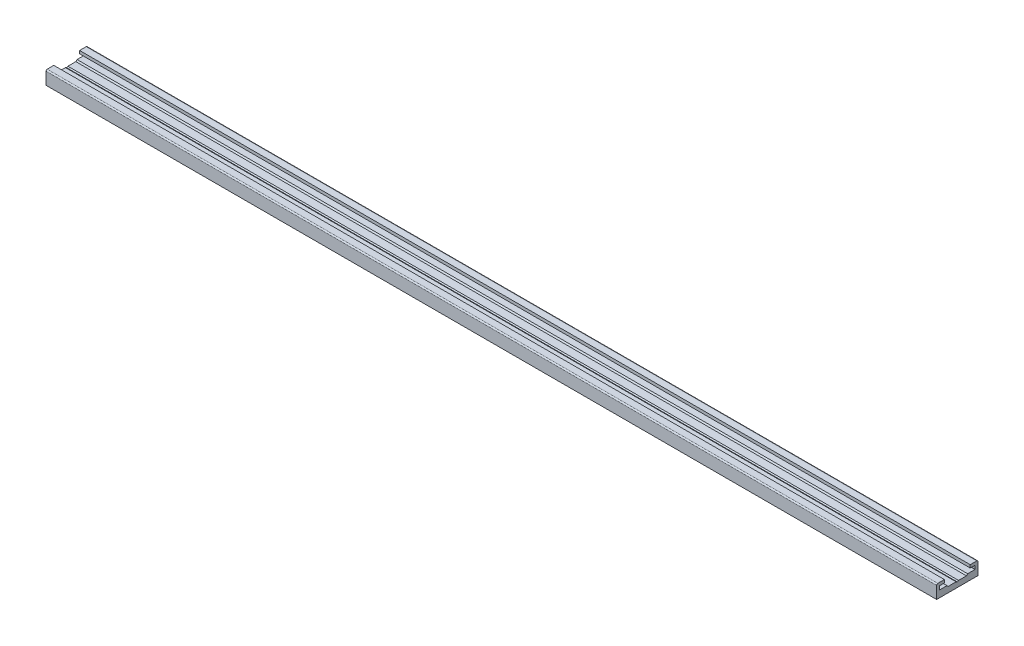
SolidWorks part; units mm, degrees
material "6061 Alloy"
ref_plane "Front" through (0, 0, 0) normal (0, 0, 1) x (1, 0, 0)
ref_plane "Top" through (0, 0, 0) normal (0, 1, 0) x (1, 0, 0)
ref_plane "Right" through (0, 0, 0) normal (1, 0, 0) x (0, 0, -1)
sketch "Sketch1" plane through (0, 0, 0) normal (1, 0, 0) x (0, 0, -1)
  line L0 (0, -2.75) -> (0, 2.75) construction
  line L1 (-0.5, -0.45) -> (0, -0.7387) construction
  line L2 (-3.75, -0.45) -> (-0.5, -0.45) construction
  line L3 (-4.25, 0.05) -> (-3.75, -0.45) construction
  line L4 (-7.3, 0.05) -> (-4.25, 0.05) construction
  line L5 (-7.3, 1.55) -> (-7.3, 0.05) construction
  line L6 (-5.3, 1.55) -> (-7.3, 1.55) construction
  line L7 (-5.3, 2.75) -> (-5.3, 1.55) construction
  line L8 (-8, 2.75) -> (-5.3, 2.75) construction
  line L9 (-8.5, -2.75) -> (-8.5, 2.25) construction
  line L39 (-8.5, -2.75) -> (8.5, -2.75) construction
  line L40 (8.5, -2.75) -> (8.5, 2.25) construction
  line L41 (8, 2.75) -> (5.3, 2.75) construction
  line L42 (5.3, 2.75) -> (5.3, 1.55) construction
  line L43 (5.3, 1.55) -> (7.3, 1.55) construction
  line L44 (7.3, 1.55) -> (7.3, 0.05) construction
  line L45 (7.3, 0.05) -> (4.25, 0.05) construction
  line L46 (4.25, 0.05) -> (3.75, -0.45) construction
  line L47 (3.75, -0.45) -> (0.5, -0.45) construction
  line L48 (0.5, -0.45) -> (0, -0.7387) construction
  arc A0 (8, 2.75) -> (8.5, 2.25) centre (8, 2.25) cw construction
  arc A1 (-8, 2.75) -> (-8.5, 2.25) centre (-8, 2.25) ccw construction
  point P1 (7.3, 0.8)
  point P26 (0, 0)
  point P32 (0, -1.75)
  dimension "D12" = 0.5
  dimension "D1" = 30
  dimension "D3" = 2.3
  dimension "Rail Height" = 5.5
  dimension "D4" = 2.0113
  dimension "D5" = 2.8
  dimension "D7" = 1.2
  dimension "D8" = 3.2
  dimension "D9" = 1.2
  dimension "D10" = 45
  dimension "D11" = 3.75
  dimension "Rail Width" = 17
  dimension "Mounting Hole Depth" = 1
sketch "Sketch2" plane through (0, 0, 0) normal (0, 0, 1) x (1, 0, 0)
  line L0 (1000, 0) -> (-1000, 0) construction
  point P0 (-960, 0)
  point P3 (-900, 0)
  point P4 (0, 0)
  point P6 (-884, 0)
  point P7 (988, 0)
  dimension "Rail Length" = 2000
  dimension "Mounting Hole Ctr to End" = 40
  dimension "Mounting Hole Ctr to Ctr" = 60
  dimension "D2" = 12
  dimension "D1" = 16
sketch "Sketch5" plane through (0, 0, 0) normal (1, 0, 0) x (0, 0, -1)
  line L0 (-8.5, -2.75) -> (8.5, -2.75) construction
  line L1 (8.5, -2.75) -> (8.5, 2.25) construction
  line L2 (8, 2.75) -> (5.3, 2.75) construction
  line L3 (5.3, 2.75) -> (5.3, 1.55) construction
  line L4 (5.3, 1.55) -> (7.3, 1.55) construction
  line L5 (7.3, 1.55) -> (7.3, 0.05) construction
  line L6 (7.3, 0.05) -> (4.25, 0.05) construction
  line L7 (4.25, 0.05) -> (3.75, -0.45) construction
  line L8 (3.75, -0.45) -> (0.5, -0.45) construction
  line L9 (0.5, -0.45) -> (0, -0.7387) construction
  line L10 (-0.5, -0.45) -> (0, -0.7387) construction
  line L11 (-3.75, -0.45) -> (-0.5, -0.45) construction
  line L12 (-4.25, 0.05) -> (-3.75, -0.45) construction
  line L13 (-7.3, 0.05) -> (-4.25, 0.05) construction
  line L14 (-7.3, 1.55) -> (-7.3, 0.05) construction
  line L15 (-5.3, 1.55) -> (-7.3, 1.55) construction
  line L16 (-5.3, 2.75) -> (-5.3, 1.55) construction
  line L17 (-8, 2.75) -> (-5.3, 2.75) construction
  line L18 (-8.5, -2.75) -> (-8.5, 2.25) construction
  line L19 (-8.5, -2.75) -> (8.5, -2.75)
  line L20 (8.5, -2.75) -> (8.5, 2.25)
  line L21 (8, 2.75) -> (5.3, 2.75)
  line L22 (5.3, 2.75) -> (5.3, 1.55)
  line L23 (5.3, 1.55) -> (7.3, 1.55)
  line L24 (7.3, 1.55) -> (7.3, 0.05)
  line L25 (7.3, 0.05) -> (4.25, 0.05)
  line L26 (4.25, 0.05) -> (3.75, -0.45)
  line L27 (3.75, -0.45) -> (0.5, -0.45)
  line L28 (0.5, -0.45) -> (0, -0.7387)
  line L29 (-0.5, -0.45) -> (0, -0.7387)
  line L30 (-3.75, -0.45) -> (-0.5, -0.45)
  line L31 (-4.25, 0.05) -> (-3.75, -0.45)
  line L32 (-7.3, 0.05) -> (-4.25, 0.05)
  line L33 (-7.3, 1.55) -> (-7.3, 0.05)
  line L34 (-5.3, 1.55) -> (-7.3, 1.55)
  line L35 (-5.3, 2.75) -> (-5.3, 1.55)
  line L36 (-8, 2.75) -> (-5.3, 2.75)
  line L37 (-8.5, -2.75) -> (-8.5, 2.25)
  arc A0 (8.5, 2.25) -> (8, 2.75) centre (8, 2.25) ccw construction
  arc A1 (-8, 2.75) -> (-8.5, 2.25) centre (-8, 2.25) ccw construction
  arc A2 (8.5, 2.25) -> (8, 2.75) centre (8, 2.25) ccw
  arc A3 (-8, 2.75) -> (-8.5, 2.25) centre (-8, 2.25) ccw
extrude "Boss-Extrude1" add sketch "Sketch5" along normal blind 366
sketch "Sketch3" plane through (0, 0, 0) normal (0, 0, 1) x (1, 0, 0)
  line L0 (-963.25, -0.45) -> (-963.25, -1.75)
  line L1 (-963.25, -1.75) -> (-961.75, -1.75)
  line L2 (-961.75, -1.75) -> (-961.75, -2.75)
  line L3 (-961.75, -2.75) -> (-960, -2.75)
  line L4 (-960, -2.75) -> (-960, -0.45)
  line L5 (-960, -0.45) -> (-963.25, -0.45)
  line L8 (-963.25, -0.45) -> (-956.75, -0.45) construction
  line L10 (-958.25, -2.75) -> (-961.75, -2.75) construction
  line L19 (366, -2.75) -> (0, -2.75) construction
  dimension "D1" = 1.3
  dimension "D2" = 6.5
  dimension "D3" = 3.5
revolve "Cut-Revolve1" [suppressed] cut sketch "Sketch3" angle 360 mid plane about L4
pattern_linear "LPattern1" [suppressed]
equation "\"D3@LPattern1\"=\"Mounting Hole Ctr to Ctr@Sketch2\""
equation "\"D2@Sketch2\"=\"Mounting Hole Ctr to End@Sketch2\"*.3"
equation "\"D1@Sketch2\"=\"Mounting Hole Ctr to End@Sketch2\"*.4"
